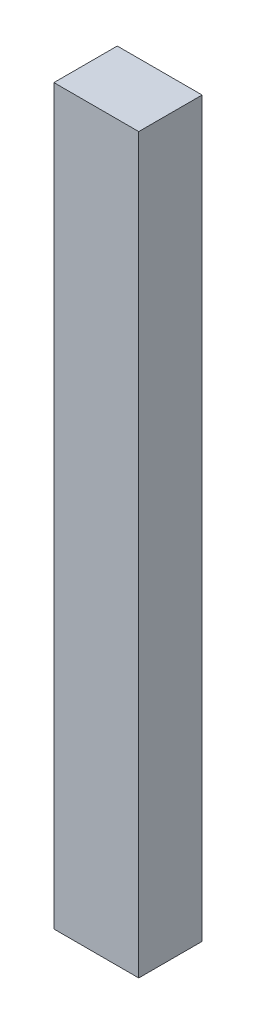
SolidWorks part; units mm, degrees
ref_plane "Front Plane" through (0, 0, 0) normal (0, 0, 1) x (1, 0, 0)
ref_plane "Top Plane" through (0, 0, 0) normal (0, 1, 0) x (1, 0, 0)
ref_plane "Right Plane" through (0, 0, 0) normal (1, 0, 0) x (0, 0, -1)
sketch "Sketch1" plane through (0, 0, 0) normal (0, 1, 0) x (1, 0, 0)
  line L0 (-27.8321, 19.4041) -> (30.9681, 19.4041)
  line L1 (30.9681, 19.4041) -> (30.9681, -24.5001)
  line L2 (30.9681, -24.5001) -> (-27.8321, -24.5001)
  line L3 (-27.8321, -24.5001) -> (-27.8321, 19.4041)
extrude "Boss-Extrude1" add sketch "Sketch1" along normal blind 508
